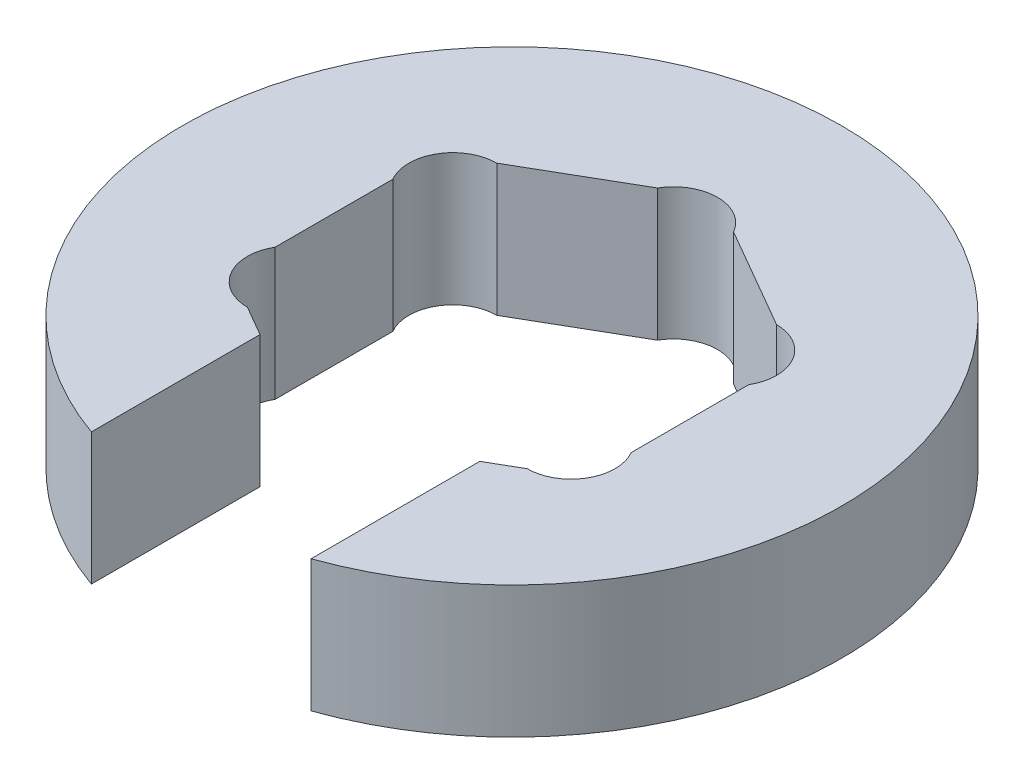
SolidWorks part; units mm, degrees
ref_plane "정면" through (0, 0, 0) normal (0, 0, 1) x (1, 0, 0)
ref_plane "윗면" through (0, 0, 0) normal (0, 1, 0) x (1, 0, 0)
ref_plane "우측면" through (0, 0, 0) normal (1, 0, 0) x (0, 0, -1)
sketch "스케치3" plane through (0, 0, 0) normal (0, 1, 0) x (1, 0, 0)
  circle A0 centre (0, 0) radius 7.5
  dimension "D1" = 15
extrude "보스-돌출2" add sketch "스케치3" along normal blind 3
sketch "스케치4" plane through (0, 3, 0) normal (0, 1, 0) x (1, 0, 0)
  line L1 (4.05, 2.3383) -> (0, 4.6765)
  line L2 (0, 4.6765) -> (-4.05, 2.3383)
  line L3 (-4.05, 2.3383) -> (-4.05, -2.3383)
  line L4 (-4.05, -2.3383) -> (0, -4.6765)
  line L5 (0, -4.6765) -> (4.05, -2.3383)
  line L6 (4.05, -2.3383) -> (4.05, 2.3383)
  circle A0 centre (0, 0) radius 4.05 construction
  dimension "D1" = 8.1
extrude "컷-돌출1" cut sketch "스케치4" against normal blind 5
sketch "스케치5" plane through (0, 3, 0) normal (0, 1, 0) x (1, 0, 0)
  line L0 (0, 3.6765) -> (0, 4.6765) construction
  circle A0 centre (0, 3.6765) radius 1
  dimension "D1" = 2
extrude "컷-돌출2" cut sketch "스케치5" against normal blind 5
sketch3d "3D스케치1"
  line L0 (0, 0, 0) -> (0, -10, 0) construction
pattern_circular "원형 패턴1" count 6 over 360 about axis through (0, 0, 0) along (0, 1, 0) of "컷-돌출2"
sketch "스케치6" plane through (0, 3, 0) normal (0, 1, 0) x (1, 0, 0)
  line L0 (0, -8.0655) -> (0, -2.7747) construction
  line L1 (-2.5, -8.0655) -> (-2.5, -2.7747)
  line L2 (2.5, -8.0655) -> (2.5, -2.7747)
  arc A0 (-2.5, -8.0655) -> (2.5, -8.0655) centre (0, -8.0655) ccw
  arc A1 (2.5, -2.7747) -> (-2.5, -2.7747) centre (0, -2.7747) ccw
  point P3 (0, -5.4201)
  dimension "D1" = 2.5
extrude "컷-돌출3" cut sketch "스케치6" against normal blind 10
